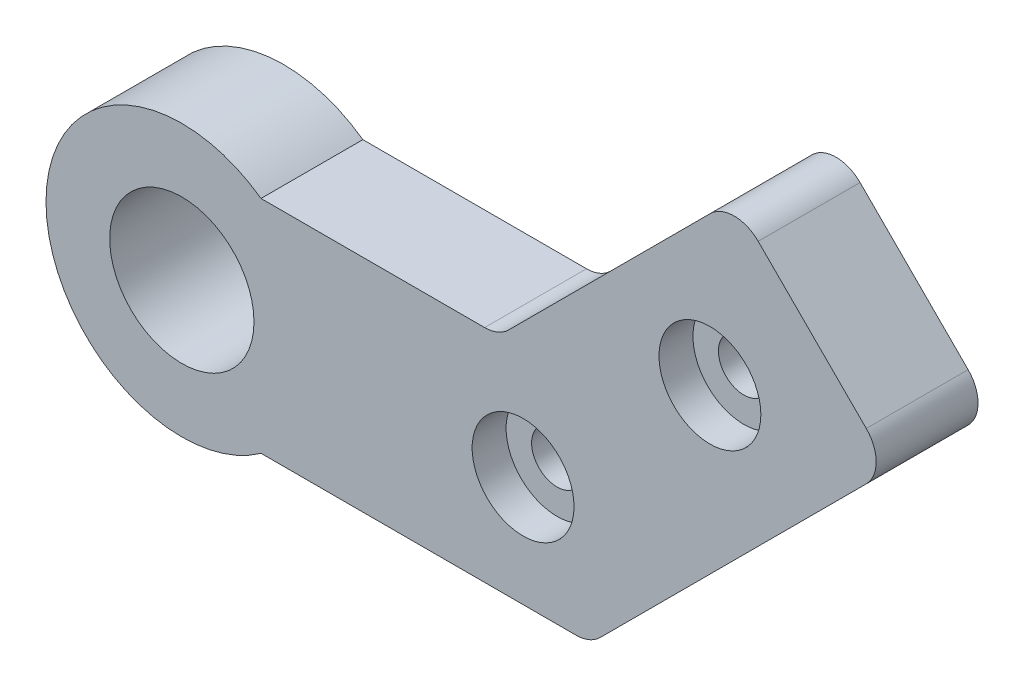
SolidWorks part; units mm, degrees
ref_plane "Plan de face" through (0, 0, 0) normal (0, 0, 1) x (1, 0, 0)
ref_plane "Plan de dessus" through (0, 0, 0) normal (0, 1, 0) x (1, 0, 0)
ref_plane "Plan de droite" through (0, 0, 0) normal (1, 0, 0) x (0, 0, -1)
sketch "Esquisse1" plane through (0, 0, 0) normal (0, 0, 1) x (1, 0, 0)
  line L0 (0.3764, -5.0463) -> (2.6727, -7.3427) construction
  line L1 (-16.7121, 5.6573) -> (-2.7121, 5.6573)
  line L3 (-16.7121, -7.3427) -> (2.6727, -7.3427)
  line L4 (-27.299, -0.8427) -> (21.5919, -0.8427) construction
  line L7 (-2.7121, 5.6573) -> (11.158, 19.5274)
  line L8 (2.6727, -7.3427) -> (20.3504, 10.335)
  line L9 (11.158, 19.5274) -> (20.3504, 10.335)
  arc A0 (-16.7121, 5.6573) -> (-16.7121, -7.3427) centre (-21.3758, -0.8427) ccw
  point P0 (0, 0)
  dimension "D6" = 8
  dimension "D1" = 13
  dimension "D2" = 45
  dimension "D3" = 25
  dimension "D4" = 14
  dimension "D5" = 13
extrude "Boss.-Extru.1" add sketch "Esquisse1" along normal blind 6
fillet "Congé1" radius 2 4 edges at (11.158, 19.5274, 3) (20.3504, 10.335, 3) (2.6727, -7.3427, 3) (-2.7121, 5.6573, 3)
sketch "Esquisse2" plane through (0, 0, 6) normal (0, 0, 1) x (1, 0, 0)
  line L0 (-1.2758, -0.8427) -> (15.7542, 14.9312) construction
  line L2 (-43.7586, -0.8427) -> (6.2431, -0.8427) construction
  line L4 (-17.7116, 6.2689) -> (-25.0399, -7.9542) construction
  line L5 (18.9361, 11.7492) -> (12.5722, 18.1132) construction
  circle A0 centre (-21.3758, -0.8427) radius 4.25
  circle A1 centre (-1.2758, -0.8427) radius 1.5
  circle A2 centre (9.7289, 9.3503) radius 1.5
  arc A3 (-16.7121, 5.6573) -> (-16.7121, -7.3427) centre (-21.3758, -0.8427) ccw construction
  dimension "D1" = 8.5
  dimension "D2" = 3
  dimension "D4" = 3
  dimension "D5" = 20.1
  dimension "D6" = 15
extrude "Enlèv. mat.-Extru.1" cut sketch "Esquisse2" against normal through all
sketch "Esquisse3" plane through (0, 0, 6) normal (0, 0, 1) x (1, 0, 0)
  circle A0 centre (-1.2758, -0.8427) radius 3
  circle A1 centre (9.7289, 9.3503) radius 3
  dimension "D1" = 6
  dimension "D2" = 6
extrude "Enlèv. mat.-Extru.2" cut sketch "Esquisse3" against normal blind 2
